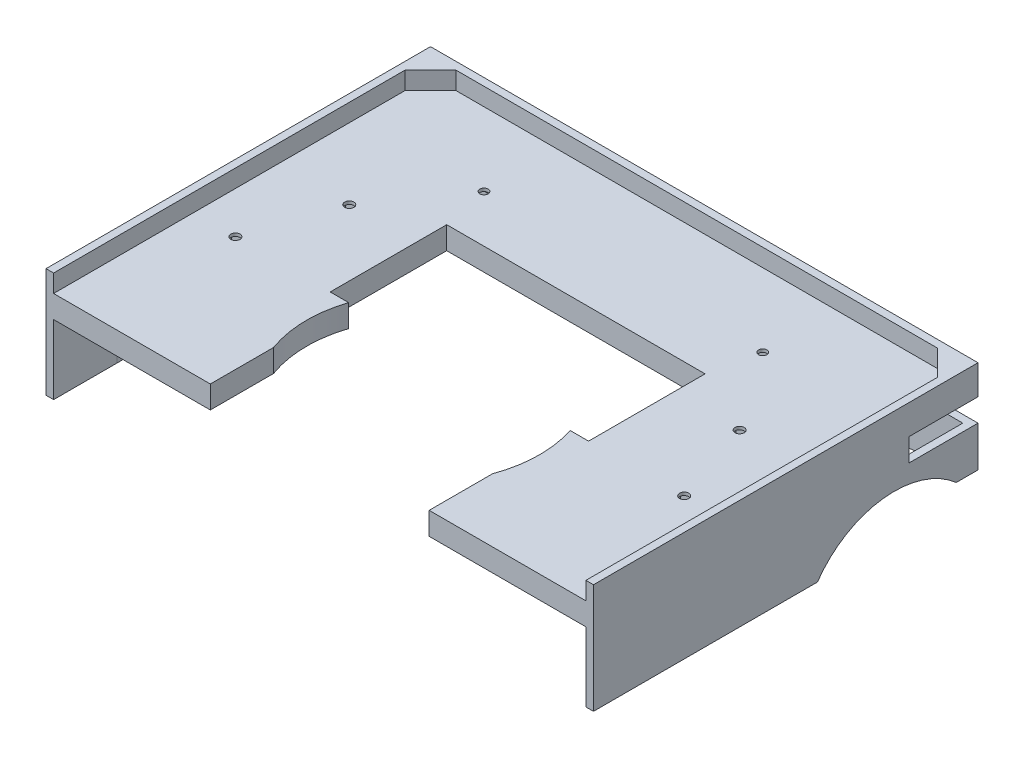
SolidWorks part; units mm, degrees
ref_plane "Alzado" through (0, 0, 0) normal (0, 0, 1) x (1, 0, 0)
ref_plane "Planta" through (0, 0, 0) normal (0, 1, 0) x (1, 0, 0)
ref_plane "Vista lateral" through (0, 0, 0) normal (1, 0, 0) x (0, 0, -1)
sketch "Croquis1" plane through (0, 0, 0) normal (0, 1, 0) x (1, 0, 0)
  line L1 (0, 0) -> (216.14, 0)
  line L2 (0, 0) -> (0, 126.8)
  line L3 (0, 126.8) -> (216.14, 126.8)
  line L4 (216.14, 0) -> (216.14, 126.8)
  dimension "D1" = 126.8
  dimension "D2" = 216.14
extrude "Saliente-Extruir1" add sketch "Croquis1" along normal blind 15.9
sketch "Croquis5" plane through (0, 15.9, 0) normal (0, 1, 0) x (1, 0, 0)
  line L0 (108.07, 126.8) -> (108.07, 0) construction
  line L1 (216.14, 126.8) -> (0, 126.8) construction
  line L2 (0, 0) -> (216.14, 0) construction
  line L3 (0, 63.4) -> (216.14, 63.4) construction
  line L4 (0, 126.8) -> (0, 0) construction
  line L5 (216.14, 0) -> (216.14, 126.8) construction
  line L7 (3, 123.8) -> (213.14, 123.8)
  line L8 (3, 123.8) -> (3, 3)
  line L9 (3, 3) -> (213.14, 3)
  line L10 (213.14, 123.8) -> (213.14, 3)
  point P16 (108.07, 123.8)
  point P17 (3, 63.4)
  dimension "D1" = 3
  dimension "D2" = 3
extrude "Cortar-Extruir2" cut sketch "Croquis5" against normal blind 7
sketch "Croquis3" plane through (0, 15.9, 0) normal (0, 1, 0) x (1, 0, 0)
  line L0 (108.07, 126.8) -> (108.07, -246.6965) construction
  line L1 (216.14, 126.8) -> (0, 126.8) construction
  line L2 (92.87, -246.6965) -> (123.27, -246.6965) construction
  line L3 (71.82, 15.808) -> (144.32, 15.808) construction
  arc A0 (143.4099, 7.7361) -> (80.9095, -8.1997) centre (108.07, 15.808) ccw construction
  circle A1 centre (108.07, 15.808) radius 46
  dimension "D1" = 92
extrude "Cortar-Extruir1" cut sketch "Croquis3" against normal through all
sketch "Croquis6" plane through (0, 0, 0) normal (0, -1, 0) x (-1, 0, 0)
  line L0 (-108.07, 126.8) -> (-108.07, -24.6967) construction
  circle A0 centre (-196.658, 30.3033) radius 1.825
  circle A1 centre (-185.1229, 63.7133) radius 1.825
  circle A2 centre (-31.0171, 63.7133) radius 1.825
  circle A3 centre (-19.482, 30.3033) radius 1.825
  circle A4 centre (-53.0665, 94.8583) radius 1.65
  circle A5 centre (-163.0735, 94.8583) radius 1.65
  dimension "D1" = 3.65
  dimension "D2" = 3.65
  dimension "D3" = 3.3
extrude "Cortar-Extruir3" cut sketch "Croquis6" against normal through all
sketch "Croquis7" plane through (0, 0, 0) normal (0, -1, 0) x (1, 0, 0)
  line L0 (216.14, 0) -> (213.14, 0)
  line L1 (151.2685, 0) -> (216.14, 0) construction
  line L2 (213.14, 0) -> (213.14, -123.8)
  line L3 (213.14, -123.8) -> (3, -123.8)
  line L4 (3, -123.8) -> (3, 0)
  line L5 (0, 0) -> (64.8715, 0) construction
  line L6 (3, 0) -> (0, 0)
  line L7 (0, 0) -> (0, -126.8)
  line L8 (0, -126.8) -> (216.14, -126.8)
  line L9 (216.14, -126.8) -> (216.14, 0)
  dimension "D1" = 3
  dimension "D2" = 3
  dimension "D3" = 3
extrude "Saliente-Extruir2" add sketch "Croquis7" along normal up to surface (27.4 mm away)
sketch "Croquis8" plane through (216.14, 0, 0) normal (1, 0, 0) x (0, 0, -1)
  line L0 (0, -27.4) -> (126.8, -27.4) construction
  line L1 (124.1343, -27.4) -> (63.4, -27.4)
  arc A0 (63.4, -27.4) -> (124.1343, -27.4) centre (93.7671, -48.5385) cw
  dimension "D1" = 37
  dimension "D2" = 2.6657
extrude "Cortar-Extruir4" cut sketch "Croquis8" against normal through all
sketch "Croquis9" plane through (0, 0, -126.8) normal (0, 0, -1) x (-1, 0, 0)
  line L0 (-216.14, -20.764) -> (-166.0277, -27.4)
  line L1 (-216.14, 15.9) -> (-216.14, -27.4) construction
  line L2 (-216.14, -27.4) -> (0, -27.4) construction
  line L3 (-108.07, -27.4) -> (-108.07, 15.9) construction
  line L4 (-216.14, 15.9) -> (0, 15.9) construction
  line L5 (-132.1965, -31.88) -> (-166.0277, -27.4) construction
  line L6 (-166.0277, -27.4) -> (-216.14, -27.4)
  line L7 (-216.14, -27.4) -> (-216.14, -20.764)
  line L8 (-50.1123, -27.4) -> (0, -27.4)
  line L9 (0, -20.764) -> (-50.1123, -27.4)
  line L10 (0, -27.4) -> (0, -20.764)
  dimension "D1" = 6.636
extrude "Cortar-Extruir5" cut sketch "Croquis9" against normal blind 10
sketch "Croquis10" plane through (0, 0, -126.8) normal (0, 0, -1) x (-1, 0, 0)
  line L0 (-166.0277, -27.4) -> (-132.1965, -31.88)
  line L1 (-132.1965, -31.88) -> (-83.9465, -31.88)
  line L2 (-83.9465, -31.88) -> (-50.1123, -27.4)
  line L3 (-50.1123, -27.4) -> (-166.0277, -27.4)
extrude "Saliente-Extruir3" add sketch "Croquis10" against normal up to surface (3 mm away) up to face at (108.07, -16.0297, -123.8)
sketch "Croquis11" plane through (0, 0, 0) normal (0, 0, 1) x (1, 0, 0)
  line L0 (108.0718, -27.4) -> (108.0718, 85.2533) construction
  line L1 (151.2685, 15.9) -> (151.2685, 0)
  line L2 (151.2685, 0) -> (213.14, 0)
  line L3 (213.14, 0) -> (213.14, -27.4)
  line L4 (213.14, -27.4) -> (216.14, -27.4)
  line L5 (216.14, -27.4) -> (216.14, 15.9)
  line L6 (216.14, 15.9) -> (151.2685, 15.9)
  line L7 (0.0036, -27.4) -> (0.0036, 15.9)
  line L8 (3.0036, -27.4) -> (0.0036, -27.4)
  line L9 (3.0036, 0) -> (3.0036, -27.4)
  line L10 (64.8751, 0) -> (3.0036, 0)
  line L11 (64.8751, 15.9) -> (64.8751, 0)
  line L12 (0.0036, 15.9) -> (64.8751, 15.9)
extrude "Saliente-Extruir4" add sketch "Croquis11" along normal blind 25
sketch "Croquis13" plane through (0, 15.9, 0) normal (0, 1, 0) x (1, 0, 0)
  line L0 (64.8751, -25) -> (64.8751, 0) construction
  line L1 (3, 3) -> (64.8751, 3)
  line L2 (3, 3) -> (3, -25)
  line L3 (3, -25) -> (64.8751, -25)
  line L4 (64.8751, 3) -> (64.8751, -25)
  line L7 (64.8751, -25) -> (0.0036, -25) construction
  line L8 (108.07, 126.8) -> (108.07, -24.6967) construction
  line L9 (216.14, 126.8) -> (0, 126.8) construction
  line L10 (213.14, -25) -> (151.2649, -25)
  line L11 (151.2649, 3) -> (151.2649, -25)
  line L12 (213.14, 3) -> (151.2649, 3)
  line L13 (213.14, 3) -> (213.14, -25)
extrude "Cortar-Extruir7" cut sketch "Croquis13" against normal up to surface (7 mm away) up to face at (196.658, 8.9, -28.4783)
sketch "Croquis16" plane through (0, 0, 0) normal (0, -1, 0) x (1, 0, 0)
  line L0 (108.0715, -126.8) -> (108.07, 24.6967) construction
  line L1 (25.0202, -59.2133) -> (37.0202, -59.2133)
  line L2 (25.0202, -59.2133) -> (25.0202, -68.2133)
  line L3 (25.0202, -68.2133) -> (37.0202, -68.2133)
  line L4 (37.0202, -59.2133) -> (37.0202, -68.2133)
  line L5 (132.1965, -126.8) -> (83.9465, -126.8) construction
  line L6 (58.5665, -91.1233) -> (47.5665, -91.1233) construction
  line L7 (11.485, -23.8033) -> (27.485, -23.8033)
  line L8 (11.485, -23.8033) -> (11.485, -36.8033)
  line L9 (11.485, -36.8033) -> (27.485, -36.8033)
  line L10 (27.485, -23.8033) -> (27.485, -36.8033)
  line L27 (47.5665, -91.1233) -> (47.5665, -83.5933) construction
  line L32 (186.5756, -82.5918) -> (186.576, -99.5918)
  line L33 (47.5665, -83.5933) -> (30.5665, -83.5933) construction
  line L34 (58.5665, -91.1233) -> (58.5665, -98.5933) construction
  line L35 (58.5665, -98.5933) -> (45.8165, -98.5933) construction
  line L36 (25.5202, -67.7133) -> (36.5202, -67.7133) construction
  line L37 (25.5202, -67.7133) -> (25.5202, -59.7133) construction
  line L38 (11.985, -24.3033) -> (11.985, -36.3033) construction
  line L39 (11.985, -36.3033) -> (26.985, -36.3033) construction
  line L44 (191.1215, -59.2117) -> (191.1217, -68.2117)
  line L45 (191.1217, -68.2117) -> (179.1217, -68.2119)
  line L46 (179.1215, -59.2119) -> (179.1217, -68.2119)
  line L47 (191.1215, -59.2117) -> (179.1215, -59.2119)
  line L48 (204.6562, -36.8014) -> (188.6562, -36.8017)
  line L49 (204.656, -23.8014) -> (204.6562, -36.8014)
  line L50 (204.656, -23.8014) -> (188.656, -23.8017)
  line L51 (188.656, -23.8017) -> (188.6562, -36.8017)
  line L52 (30.5665, -83.5933) -> (30.5665, -98.5933) construction
  line L53 (30.5665, -98.5933) -> (58.5665, -98.5933) construction
  line L54 (29.5665, -99.5933) -> (59.5665, -99.5933)
  line L55 (59.5665, -99.5933) -> (59.5665, -90.1233)
  line L56 (59.5665, -90.1233) -> (48.5665, -90.1233)
  line L57 (48.5665, -90.1233) -> (48.5665, -82.5933)
  line L58 (48.5665, -82.5933) -> (29.5665, -82.5933)
  line L59 (29.5665, -82.5933) -> (29.5665, -99.5933)
  line L60 (186.576, -99.5918) -> (156.576, -99.5924)
  line L61 (156.576, -99.5924) -> (156.5758, -90.1224)
  line L62 (156.5758, -90.1224) -> (167.5758, -90.1221)
  line L63 (167.5758, -90.1221) -> (167.5756, -82.5921)
  line L64 (167.5756, -82.5921) -> (186.5756, -82.5918)
  point P31 (31.0202, -67.7133)
  point P33 (31.0202, -59.2133)
  point P34 (25.5202, -63.7133)
  point P43 (25.0202, -63.7133)
  point P44 (19.485, -23.8033)
  point P51 (19.485, -36.3033)
  point P52 (11.985, -30.3033)
  point P53 (11.485, -30.3033)
  dimension "D1" = 1
  dimension "D2" = 1
  dimension "D3" = 9
  dimension "D4" = 12
  dimension "D5" = 13
  dimension "D6" = 16
  dimension "D7" = 1
  dimension "D8" = 1
  dimension "D9" = 1
  dimension "D10" = 1
extrude "Cortar-Extruir8" cut sketch "Croquis16" against normal blind 7.7
chamfer "Chaflán1" distance 10 angle 45 2 edges at (3, 12.4, -123.8) (213.14, 12.4, -123.8)
sketch "Croquis21" plane through (0, 0, 0) normal (0, -1, 0) x (1, 0, 0)
  line L0 (85.4465, -91.1233) -> (41.0715, -91.1233) construction
  line L1 (57.0716, -30.1233) -> (159.0716, -30.1233)
  line L2 (57.0716, -30.1233) -> (57.0716, -76.1233)
  line L3 (57.0716, -76.1233) -> (159.0716, -76.1233)
  line L4 (159.0716, -30.1233) -> (159.0716, -76.1233)
  line L5 (108.0715, -126.8) -> (108.0718, 292.6965) construction
  line L6 (132.1965, -126.8) -> (83.9465, -126.8) construction
  line L7 (57.8601, 292.6965) -> (158.2835, 292.6965) construction
  point P12 (108.0716, -30.1233)
  dimension "D1" = 15
  dimension "D2" = 102
  dimension "D3" = 46
extrude "Cortar-Extruir10" cut sketch "Croquis21" against normal through all
sketch "Croquis22" plane through (0, 0, -126.8) normal (0, 0, -1) x (-1, 0, 0)
  line L0 (-177.0765, 4.25) -> (-216.14, 4.25)
  line L1 (-216.14, 15.9) -> (-216.14, -20.764) construction
  line L2 (-216.14, 4.25) -> (-216.14, -4.75)
  line L3 (-216.14, -4.75) -> (-177.0765, -4.75)
  line L4 (-108.0715, -31.88) -> (-108.07, 15.9) construction
  line L5 (-132.1965, -31.88) -> (-83.9465, -31.88) construction
  line L6 (-216.14, 15.9) -> (0, 15.9) construction
  line L7 (-0.0013, -4.7568) -> (-39.0648, -4.7544)
  line L8 (-0.0007, 4.2432) -> (-0.0013, -4.7568)
  line L9 (-39.0642, 4.2456) -> (-0.0007, 4.2432)
  circle A0 centre (-177.0765, -0.25) radius 4.5 construction
  arc A1 (-177.0765, -4.75) -> (-177.0765, 4.25) centre (-177.0765, -0.25) ccw
  arc A2 (-39.0648, -4.7544) -> (-39.0642, 4.2456) centre (-39.0645, -0.2544) cw
  dimension "D1" = 39.0635
extrude "Cortar-Extruir11" cut sketch "Croquis22" against normal up to surface (27.2067 mm away) up to face at (44.5665, 3.85, -99.5933)
sketch "Croquis23" plane through (0.001, 0, 0) normal (1, 0.0001, 0) x (0, 0, -1)
  line L1 (99.5933, 4.2364) -> (126.8, 4.2364)
  line L2 (99.5933, 4.2364) -> (99.5933, -4.7636)
  line L3 (99.5933, -4.7636) -> (126.8, -4.7636)
  line L4 (126.8, 4.2364) -> (126.8, -4.7636)
extrude "Cortar-Extruir12" cut sketch "Croquis23" against normal through all
sketch "Croquis25" plane through (0, 0, 0) normal (-1, 0, 0) x (0, 0, 1)
  line L1 (-99.5933, 4.2364) -> (-123.8, 4.2364)
  line L2 (-99.5933, 4.2364) -> (-99.5933, 0)
  line L3 (-99.5933, 0) -> (-123.8, 0)
  line L4 (-123.8, 4.2364) -> (-123.8, 0)
extrude "Cortar-Extruir16" cut sketch "Croquis25" against normal blind 50
sketch "Croquis26" plane through (216.14, 0, 0) normal (1, 0, 0) x (0, 0, -1)
  line L1 (99.5933, 4.25) -> (123.8, 4.25)
  line L2 (99.5933, 4.25) -> (99.5933, 0)
  line L3 (99.5933, 0) -> (123.8, 0)
  line L4 (123.8, 4.25) -> (123.8, 0)
extrude "Cortar-Extruir17" cut sketch "Croquis26" against normal blind 50
sketch "Croquis31" plane through (0, 0, 0) normal (0, -1, 0) x (1, 0, 0)
  line L0 (186.576, -99.5918) -> (186.5756, -82.5918) construction
  line L1 (166.14, -123.8) -> (186.5758, -123.8)
  line L2 (166.14, -123.8) -> (166.14, -91.0918)
  line L3 (166.14, -91.0918) -> (186.5758, -91.0918)
  line L4 (186.5758, -123.8) -> (186.5758, -91.0918)
extrude "Cortar-Extruir19" cut sketch "Croquis31" against normal up to surface (4.25 mm away) up to face at (186.4522, 4.25, -116.7311)
sketch "Croquis32" plane through (-0.0003, 4.2432, 0) normal (0.0001, -1, 0) x (1, 0.0001, 0)
  line L1 (39.3538, -99.5933) -> (-0.0013, -99.5933)
  line L2 (39.3538, -99.5933) -> (39.3538, -126.8)
  line L3 (39.3538, -126.8) -> (-0.0013, -126.8)
  line L4 (-0.0013, -99.5933) -> (-0.0013, -126.8)
extrude "Cortar-Extruir20" cut sketch "Croquis32" along normal up to surface (0.0093 mm away) up to face at (44.6767, 4.2364, -111.6967)
